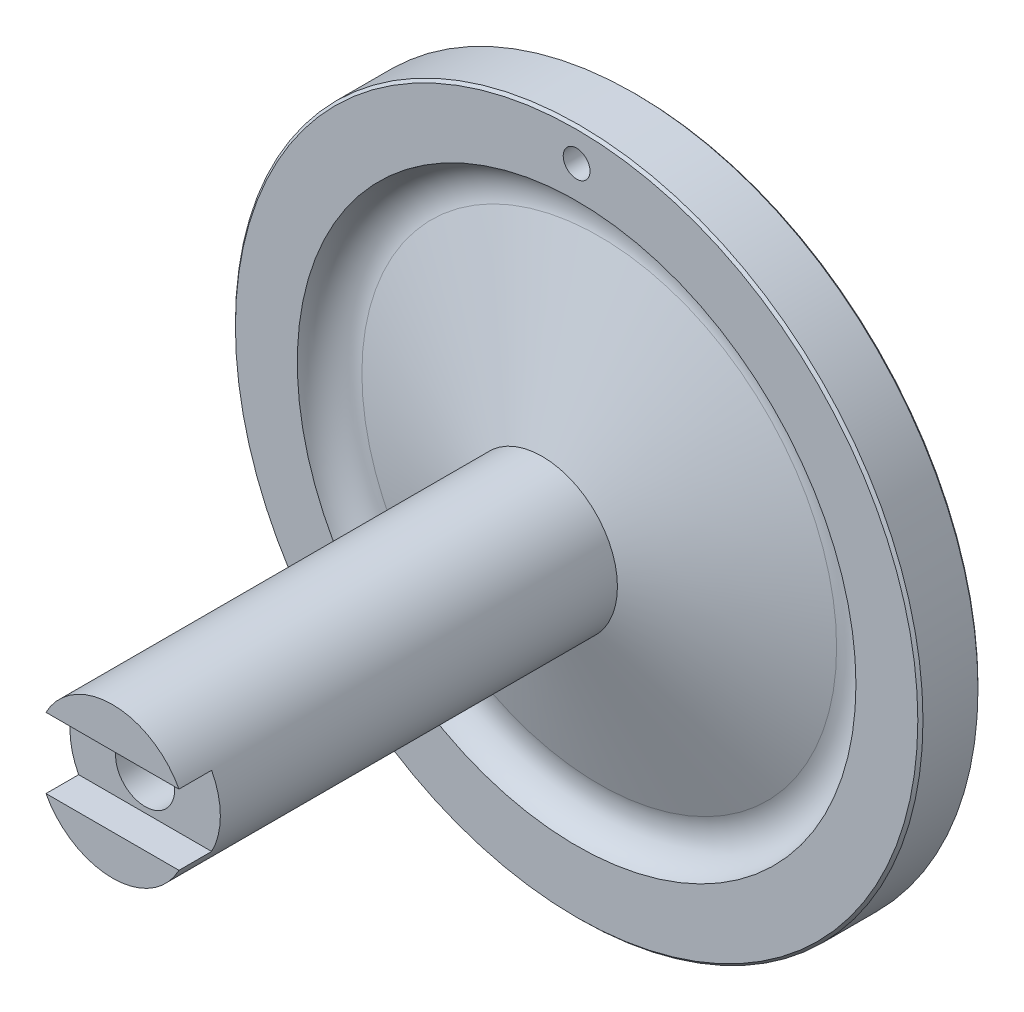
SolidWorks part; units mm, degrees
material "Malleable Cast Iron"
ref_plane "Front Plane" through (0, 0, 0) normal (0, 0, 1) x (1, 0, 0)
ref_plane "Top Plane" through (0, 0, 0) normal (0, 1, 0) x (1, 0, 0)
ref_plane "Right Plane" through (0, 0, 0) normal (1, 0, 0) x (0, 0, -1)
sketch "Sketch1" plane through (0, 0, 0) normal (1, 0, 0) x (0, 0, -1)
  line L0 (0, 0) -> (178.9077, 0) construction
  line L1 (0, 8.7376) -> (0, 22.225)
  line L2 (0, 22.225) -> (127, 22.225)
  line L3 (127, 22.225) -> (143.8484, 70.147)
  line L4 (137.16, 82.55) -> (137.16, 101.6)
  line L5 (137.16, 101.6) -> (154.94, 101.6)
  line L6 (154.94, 101.6) -> (154.94, 82.55)
  line L7 (154.94, 82.55) -> (137.8045, 33.8114)
  line L8 (147.0152, 15.875) -> (147.0152, 8.7376)
  line L9 (147.0152, 8.7376) -> (0, 8.7376)
  line L10 (0, 22.225) -> (0, 0) construction
  line L11 (139.6018, 24.4032) -> (147.0152, 15.875)
  arc A0 (143.8484, 70.147) -> (137.16, 82.55) centre (134.8625, 73.3062) ccw
  arc A2 (137.8045, 33.8114) -> (139.6018, 24.4032) centre (146.7904, 30.6522) ccw
  dimension "D1" = 203.2
  dimension "D11" = 9.525
  dimension "D13" = 49
  dimension "D14" = 9.525
  dimension "D2" = 44.45
  dimension "D3" = 31.75
  dimension "D4" = 17.4752
  dimension "D5" = 10.16
  dimension "D6" = 17.78
  dimension "D7" = 19.05
  dimension "D8" = 19.05
  dimension "D9" = 127
  dimension "D10" = 6.35
  dimension "D12" = 7.9248
revolve "Revolve1" add sketch "Sketch1" angle 360 about L0
chamfer "Chamfer1" distance 0.762 angle 45 2 edges at (101.6, 0, -154.94) (101.6, 0, -137.16)
sketch "Sketch2" plane through (0, 0, 0) normal (1, 0, 0) x (0, 0, -1)
  line L0 (54.7462, 0) -> (-54.7462, 0) construction
  line L1 (9.652, -10.3886) -> (0, -10.3886)
  line L2 (9.652, -10.3886) -> (9.652, 10.3886)
  line L3 (9.652, 10.3886) -> (0, 10.3886)
  line L4 (0, -10.3886) -> (0, 10.3886)
  line L5 (9.652, -10.3886) -> (0, 10.3886) construction
  line L6 (9.652, 10.3886) -> (0, -10.3886) construction
  line L7 (0, 54.9142) -> (0, -54.9142) construction
  point P0 (4.826, 0)
  dimension "D1" = 9.652
  dimension "D2" = 20.7772
extrude "Cut-Extrude1" cut sketch "Sketch2" against normal through all both and the other way through all
sketch "Sketch3" plane through (0, 0, -154.94) normal (0, 0, -1) x (-1, 0, 0)
  line L0 (0, 101.6) -> (0, 82.55) construction
  circle A0 centre (0, 92.075) radius 3.9624
  circle A1 centre (0, 0) radius 101.6 construction
  circle A2 centre (0, 0) radius 82.55 construction
  dimension "D1" = 7.9248
extrude "Cut-Extrude2" cut sketch "Sketch3" against normal through all
